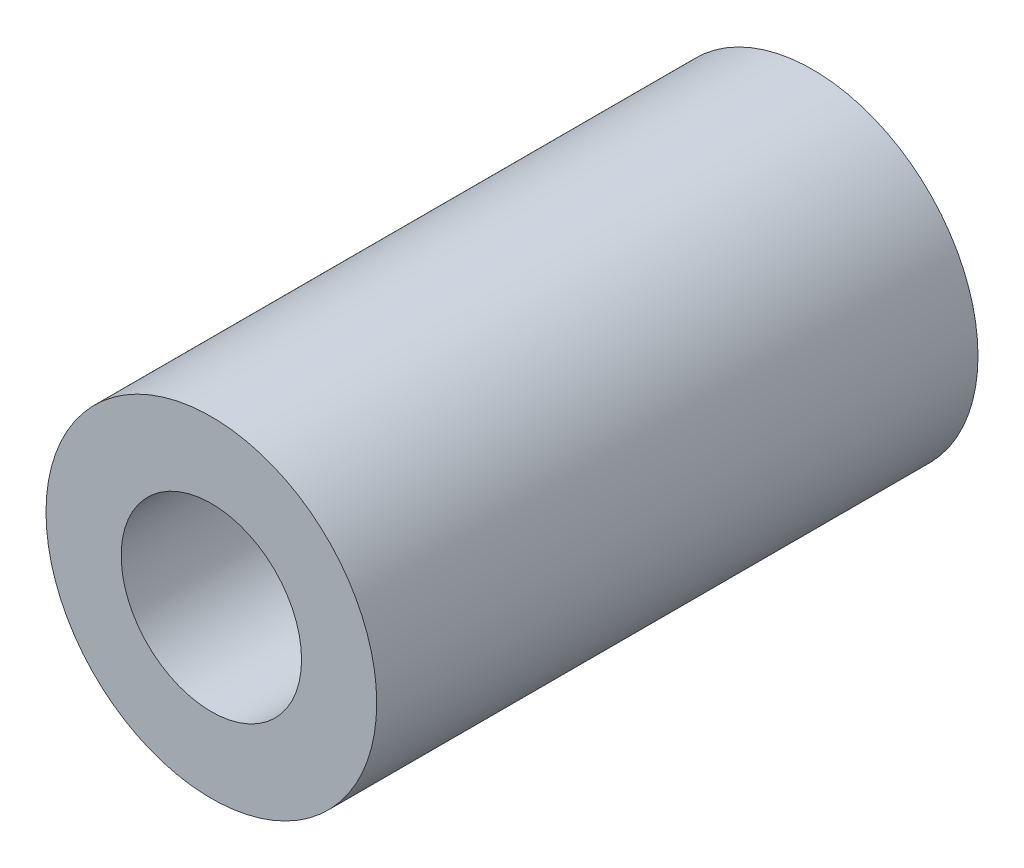
SolidWorks part; units mm, degrees
ref_plane "Front Plane" through (0, 0, 0) normal (0, 0, 1) x (1, 0, 0)
ref_plane "Top Plane" through (0, 0, 0) normal (0, 1, 0) x (1, 0, 0)
ref_plane "Right Plane" through (0, 0, 0) normal (1, 0, 0) x (0, 0, -1)
sketch "Sketch1" plane through (0, 0, 0) normal (0, 0, 1) x (1, 0, 0)
  circle A0 centre (0, 0) radius 3
  circle A1 centre (0, 0) radius 5.5
  dimension "D1" = 6
  dimension "D2" = 11
extrude "Boss-Extrude1" add sketch "Sketch1" along normal blind 20
